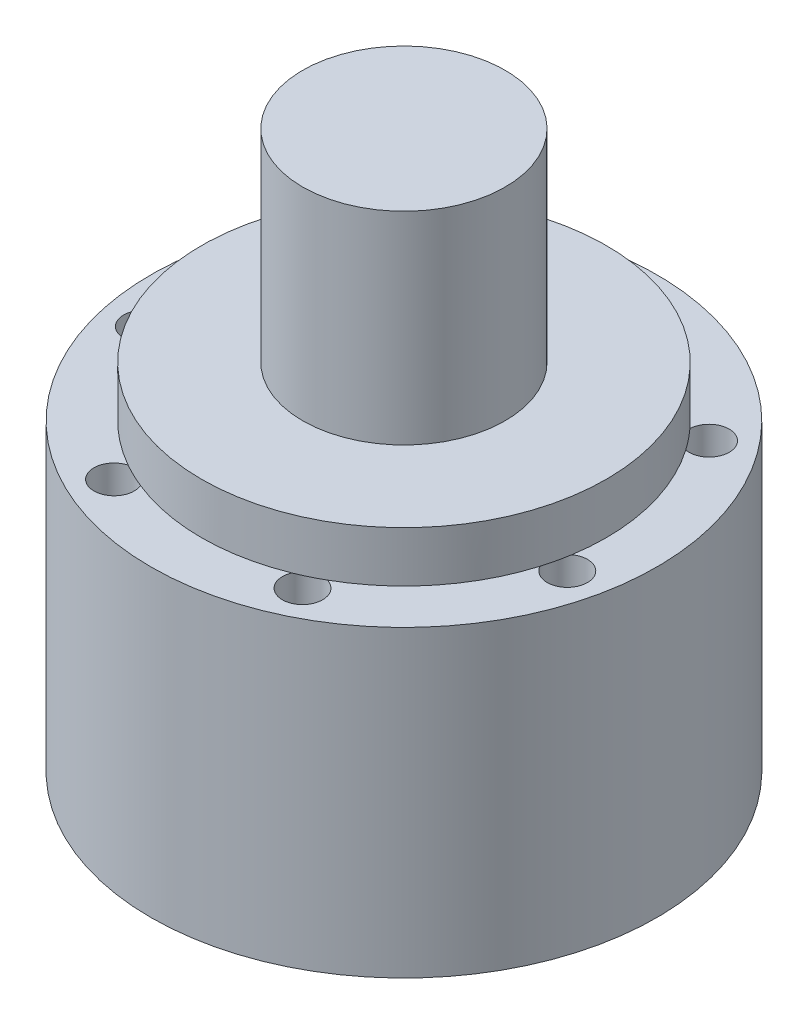
SolidWorks part; units mm, degrees
ref_plane "前视基准面" through (0, 0, 0) normal (0, 0, 1) x (1, 0, 0)
ref_plane "上视基准面" through (0, 0, 0) normal (0, 1, 0) x (1, 0, 0)
ref_plane "右视基准面" through (0, 0, 0) normal (1, 0, 0) x (0, 0, -1)
sketch "草图1" plane through (0, 0, 0) normal (0, 1, 0) x (1, 0, 0)
  circle A0 centre (0, 0) radius 25
  circle A1 centre (0, 3.5519) radius 1.326
  circle A2 centre (0, 8.193) radius 1.7075
  circle A3 centre (0, 21.4534) radius 1.9891
  circle A4 centre (0, 14.3497) radius 1.8681
  circle A5 centre (2.777, 2.2146) radius 1.326
  circle A6 centre (6.4056, 5.1083) radius 1.7075
  circle A7 centre (11.219, 8.9469) radius 1.8681
  circle A8 centre (16.773, 13.376) radius 1.9891
  circle A9 centre (3.4628, -0.7904) radius 1.326
  circle A10 centre (7.9876, -1.8231) radius 1.7075
  circle A11 centre (13.9899, -3.1931) radius 1.8681
  circle A12 centre (20.9156, -4.7738) radius 1.9891
  circle A13 centre (1.5411, -3.2001) radius 1.326
  circle A14 centre (3.5548, -7.3817) radius 1.7075
  circle A15 centre (6.2261, -12.9286) radius 1.8681
  circle A16 centre (9.3083, -19.3289) radius 1.9891
  circle A17 centre (-1.5411, -3.2001) radius 1.326
  circle A18 centre (-3.5548, -7.3817) radius 1.7075
  circle A19 centre (-6.2261, -12.9286) radius 1.8681
  circle A20 centre (-9.3083, -19.3289) radius 1.9891
  circle A21 centre (-3.4628, -0.7904) radius 1.326
  circle A22 centre (-7.9876, -1.8231) radius 1.7075
  circle A23 centre (-13.9899, -3.1931) radius 1.8681
  circle A24 centre (-20.9156, -4.7738) radius 1.9891
  circle A25 centre (-2.777, 2.2146) radius 1.326
  circle A26 centre (-6.4056, 5.1083) radius 1.7075
  circle A27 centre (-11.219, 8.9469) radius 1.8681
  circle A28 centre (-16.773, 13.376) radius 1.9891
  point P61 (0, 0)
  dimension "D2" = 50
  dimension "D1" = 7
extrude "凸台-拉伸1" add sketch "草图1" along normal blind 30
sketch "草图2" plane through (0, 30, 0) normal (0, 1, 0) x (1, 0, 0)
  circle A0 centre (0, 0) radius 20
  dimension "D1" = 40
extrude "凸台-拉伸2" add sketch "草图2" along normal blind 5
sketch "草图3" plane through (0, 35, 0) normal (0, 1, 0) x (1, 0, 0)
  circle A0 centre (0, 0) radius 10
  dimension "D1" = 20
extrude "凸台-拉伸3" add sketch "草图3" along normal blind 20
